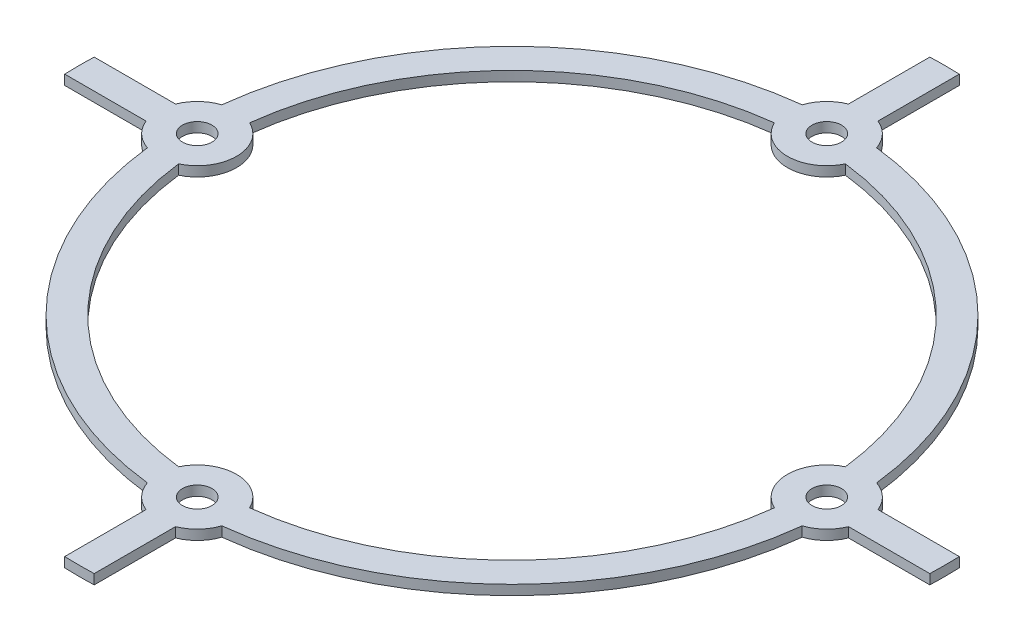
SolidWorks part; units mm, degrees
ref_plane "Front Plane" through (0, 0, 0) normal (0, 0, 1) x (1, 0, 0)
ref_plane "Top Plane" through (0, 0, 0) normal (0, 1, 0) x (1, 0, 0)
ref_plane "Right Plane" through (0, 0, 0) normal (1, 0, 0) x (0, 0, -1)
sketch "Sketch1" plane through (0, 0, 0) normal (0, 1, 0) x (1, 0, 0)
  circle A0 centre (0, 0) radius 139.7
  dimension "D1" = 279.4
extrude "Boss-Extrude1" add sketch "Sketch1" along normal blind 3.175
sketch "Sketch2" plane through (0, 3.175, 0) normal (0, 1, 0) x (1, 0, 0)
  line L0 (139.6188, 4.7625) -> (139.6188, 0) construction
  line L1 (139.6188, -4.7625) -> (113.3732, -4.7625) construction
  line L2 (139.6188, 4.7625) -> (113.3732, 4.7625)
  line L3 (0, 101.6) -> (0, 0) construction
  line L4 (0, 0) -> (139.6188, 0) construction
  line L5 (0, 88.9) -> (0, 0)
  line L6 (0, 0) -> (88.9, 0)
  line L7 (-4.7625, 113.3732) -> (-4.7625, 139.6188) construction
  line L8 (4.7625, 119.5331) -> (-4.7625, 119.5331) construction
  line L9 (4.7625, 139.6188) -> (4.7625, 113.3732)
  line L10 (0, 101.6) -> (0, 106.3625) construction
  line L11 (0, 114.3) -> (0, 129.54) construction
  line L12 (126.496, 4.7625) -> (126.496, -4.7625) construction
  circle A0 centre (0, 101.6) radius 4.7625 construction
  circle A1 centre (101.6, 0) radius 4.7625 construction
  arc A2 (113.3732, 4.7625) -> (105.6804, 12.0267) centre (101.6, 0) ccw
  arc A3 (0, 88.9) -> (11.4737, 96.1554) centre (0, 101.6) ccw
  arc A4 (105.6804, 12.0267) -> (12.0267, 105.6804) centre (0, 0) ccw
  arc A5 (96.1554, 11.4737) -> (11.4737, 96.1554) centre (0, 0) ccw
  circle A6 centre (0, 0) radius 139.7 construction
  arc A7 (96.1554, 11.4737) -> (88.9, 0) centre (101.6, 0) ccw
  arc A8 (12.0267, 105.6804) -> (4.7625, 113.3732) centre (0, 101.6) ccw
  arc A9 (139.6188, 4.7625) -> (4.7625, 139.6188) centre (0, 0) ccw
  point P13 (126.496, 0)
  point P24 (0, 119.5331)
  dimension "D1" = 9.525
  dimension "D5" = 25.4
  dimension "D2" = 101.6
  dimension "D4" = 9.525
  dimension "D6" = 101.6
  dimension "D7" = 9.525
extrude "Cut-Extrude1" cut sketch "Sketch2" against normal through all
hole_wizard "3/8 (0.375) Diameter Hole1" positions "Sketch5" profile "Sketch7" hole size "3/8" standard "ANSI Inch" end condition up to next
sketch "Sketch5" plane through (0, 3.175, 0) normal (0, 1, 0) x (1, 0, 0)
  point P0 (101.6, 0)
sketch "Sketch7" plane through (101.6, 3.175, 0) normal (1, 0, 0) x (0, 0, 1)
  line L0 (0, 0) -> (0, 3.176)
  line L1 (0, 3.176) -> (4.7625, 3.176)
  line L2 (4.7625, 3.176) -> (4.7625, 0)
  line L5 (4.7625, 0) -> (0, 0)
  line L11 (0, -6.35) -> (0, 107.95) construction
  dimension "Thru Hole Dia." = 9.525
  dimension "Thru Hole Depth" = 3.176
pattern_circular "CirPattern2" count 4 over 360 about axis through (0, 0, 0) along (0, 1, 0) of "3/8 (0.375) Diameter Hole1", "Cut-Extrude1"
equation "\"D6@Sketch2\"=\"D2@Sketch2\""
